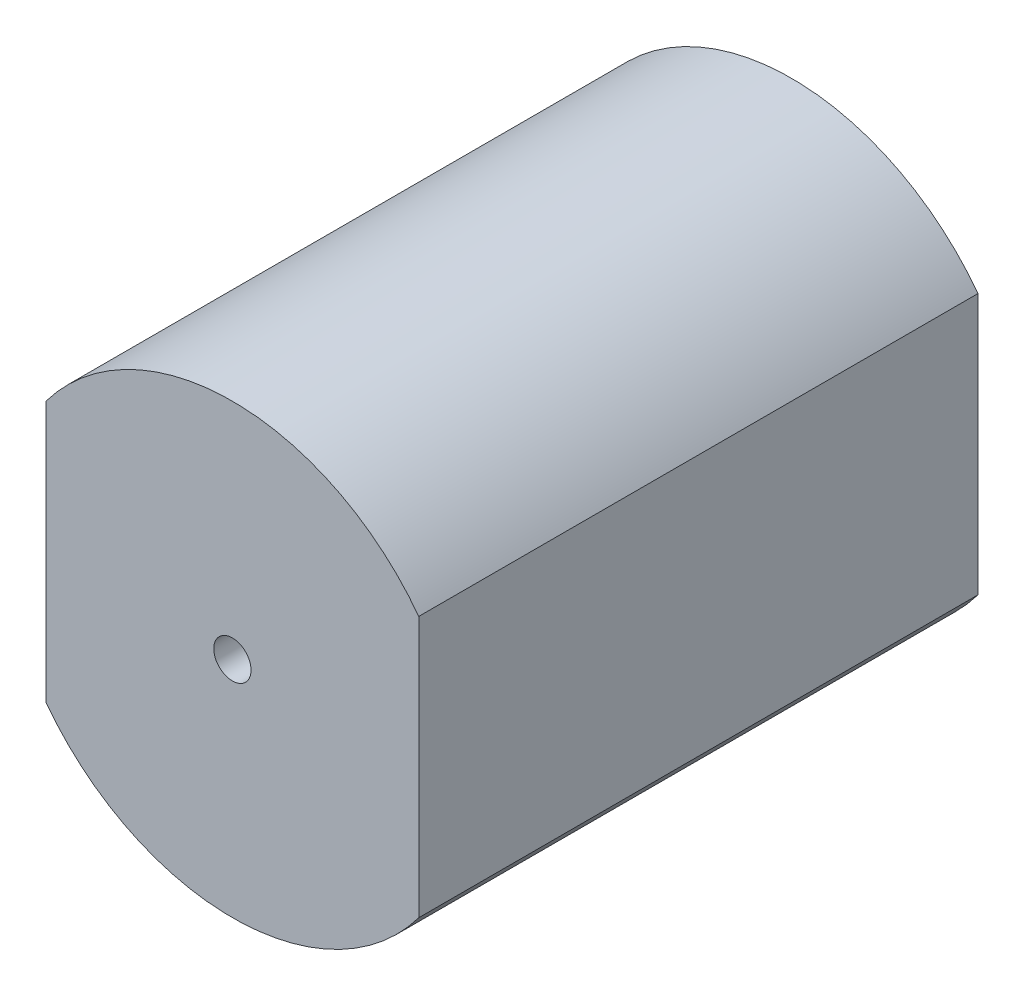
SolidWorks part; units mm, degrees
material "6061 Alloy"
ref_plane "Front Plane" through (0, 0, 0) normal (0, 0, 1) x (1, 0, 0)
ref_plane "Top Plane" through (0, 0, 0) normal (0, 1, 0) x (1, 0, 0)
ref_plane "Right Plane" through (0, 0, 0) normal (1, 0, 0) x (0, 0, -1)
sketch "Sketch1" plane through (0, 0, 0) normal (0, 0, 1) x (1, 0, 0)
  line L0 (0, 2.5) -> (0, 9.5)
  line L1 (10, 2.5) -> (10, 9.5)
  arc A0 (0, 2.5) -> (10, 2.5) centre (5, 6.25) ccw
  arc A1 (0, 9.5) -> (10, 9.5) centre (5, 5.75) cw
  point P6 (5, 0)
  point P8 (5, 12)
  dimension "D1" = 7
  dimension "D2" = 10
  dimension "D3" = 2.5
  dimension "D4" = 2.5
  dimension "D5" = 2.5
extrude "Boss-Extrude1" add sketch "Sketch1" against normal blind 15
sketch "Sketch3" plane through (0, 0, -15) normal (0, 0, -1) x (-1, 0, 0)
  line L0 (-10, 2.5) -> (-10, 9.5) construction
  circle A0 centre (-5, 6) radius 2.5
  arc A1 (0, 9.5) -> (-10, 9.5) centre (-5, 5.75) ccw construction
  point P4 (-5, 12)
  dimension "D1" = 5
  dimension "D2" = 5
  dimension "D3" = 6
extrude "Boss-Extrude2" add sketch "Sketch3" along normal blind 2
sketch "Sketch5" plane through (0, 0, -17) normal (0, 0, -1) x (-1, 0, 0)
  circle A0 centre (-5, 6) radius 0.5
  dimension "D1" = 1
extrude "Cut-Extrude1" cut sketch "Sketch5" against normal through all
fillet "Fillet1" radius 0.1 2 edges at (7.5, 6, -15) (2.5, 6, -17)
